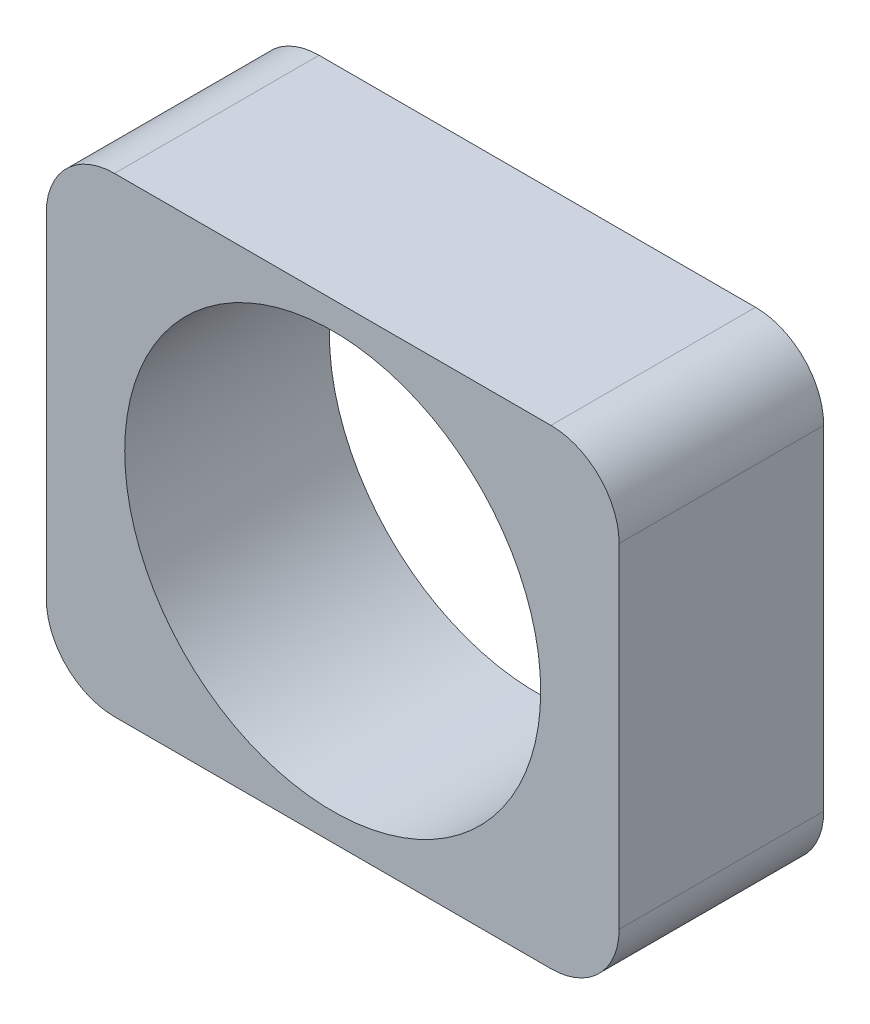
SolidWorks part; units mm, degrees
material "ABS"
ref_plane "Front Plane" through (0, 0, 0) normal (0, 0, 1) x (1, 0, 0)
ref_plane "Top Plane" through (0, 0, 0) normal (0, 1, 0) x (1, 0, 0)
ref_plane "Right Plane" through (0, 0, 0) normal (1, 0, 0) x (0, 0, -1)
sketch "Sketch1" plane through (0, 0, 0) normal (0, 0, 1) x (1, 0, 0)
  line L1 (-8.4, 6.9) -> (8.4, 6.9)
  line L2 (-8.4, 6.9) -> (-8.4, -6.9)
  line L3 (-8.4, -6.9) -> (8.4, -6.9)
  line L4 (8.4, 6.9) -> (8.4, -6.9)
  line L5 (-8.4, 6.9) -> (8.4, -6.9) construction
  line L6 (-8.4, -6.9) -> (8.4, 6.9) construction
  point P0 (0, 0)
  dimension "D1" = 16.8
  dimension "D2" = 13.8
extrude "Boss-Extrude1" add sketch "Sketch1" along normal blind 6
sketch "Sketch2" plane through (0, 0, 6) normal (0, 0, 1) x (1, 0, 0)
  circle A0 centre (0, 0) radius 6.1
  dimension "D1" = 12.2
extrude "Cut-Extrude1" cut sketch "Sketch2" against normal up to next
fillet "Fillet1" radius 2 4 edges at (8.4, -6.9, 3) (-8.4, -6.9, 3) (8.4, 6.9, 3) (-8.4, 6.9, 3)
equation "\"D1@Sketch1\"=17-\"print_fit@Parameters@FabricationParameters.sldprt\""
equation "\"D2@Sketch1\"=14-\"print_fit@Parameters@FabricationParameters.sldprt\""
equation "\"D1@Sketch2\"=12+\"print_fit@Parameters@FabricationParameters.sldprt\""
